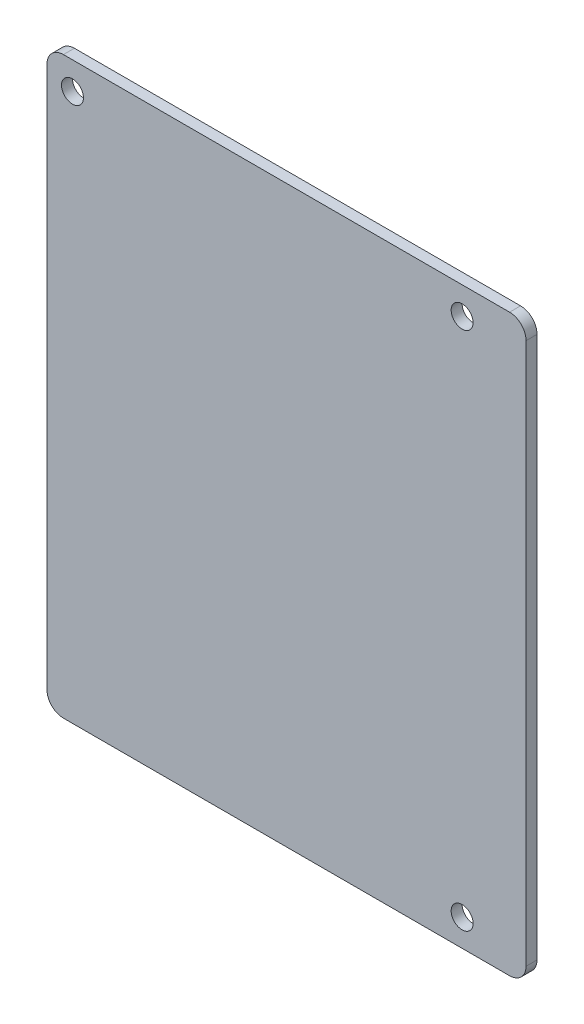
SolidWorks part; units mm, degrees
ref_plane "前视基准面" through (0, 0, 0) normal (0, 0, 1) x (1, 0, 0)
ref_plane "上视基准面" through (0, 0, 0) normal (0, 1, 0) x (1, 0, 0)
ref_plane "右视基准面" through (0, 0, 0) normal (1, 0, 0) x (0, 0, -1)
sketch "草图1" plane through (0, 0, 0) normal (0, 0, 1) x (1, 0, 0)
  line L1 (-40.65, 52.36) -> (40.65, 52.36)
  line L2 (-43.65, 49.36) -> (-43.65, -49.36)
  line L3 (-40.65, -52.36) -> (40.65, -52.36)
  line L4 (43.65, 49.36) -> (43.65, -49.36)
  line L5 (-43.65, 52.36) -> (43.65, -52.36) construction
  line L6 (-43.65, -52.36) -> (43.65, 52.36) construction
  arc A0 (-40.65, -52.36) -> (-43.65, -49.36) centre (-40.65, -49.36) cw
  arc A1 (43.65, -49.36) -> (40.65, -52.36) centre (40.65, -49.36) cw
  arc A2 (40.65, 52.36) -> (43.65, 49.36) centre (40.65, 49.36) cw
  arc A3 (-40.65, 52.36) -> (-43.65, 49.36) centre (-40.65, 49.36) ccw
  point P0 (0, 0)
  dimension "D3" = 3
  dimension "D1" = 87.3
  dimension "D2" = 104.72
extrude "凸台-拉伸1" add sketch "草图1" along normal blind 2
sketch "草图2" plane through (0, 0, 2) normal (0, 0, 1) x (1, 0, 0)
  line L0 (-43.65, 49.36) -> (-43.65, -49.36) construction
  line L1 (40.65, 52.36) -> (-40.65, 52.36) construction
  line L2 (-39, 47.36) -> (32, 47.36)
  line L3 (32, 47.36) -> (32, -47.44)
  line L4 (43.65, -49.36) -> (43.65, 49.36) construction
  point P0 (-39, 47.36)
  point P1 (32, 47.36)
  point P2 (32, -47.44)
  dimension "D1" = 4.65
  dimension "D2" = 5
  dimension "D3" = 71
  dimension "D4" = 94.8
hole_wizard "Ø4.0mm 暗销孔1" positions "草图2" profile "草图3" hole size "Ø4.0" standard "GB" end condition through all
sketch "草图3" plane through (-39, 47.36, 2) normal (1, 0, 0) x (0, -1, 0)
  line L0 (0, 0) -> (0, 2)
  line L1 (0, 2) -> (2, 2)
  line L2 (2, 2) -> (2, 0)
  line L5 (2, 0) -> (0, 0)
  line L11 (0, -6.35) -> (0, 107.95) construction
  dimension "通孔孔直径" = 4
  dimension "通孔孔深度" = 2
